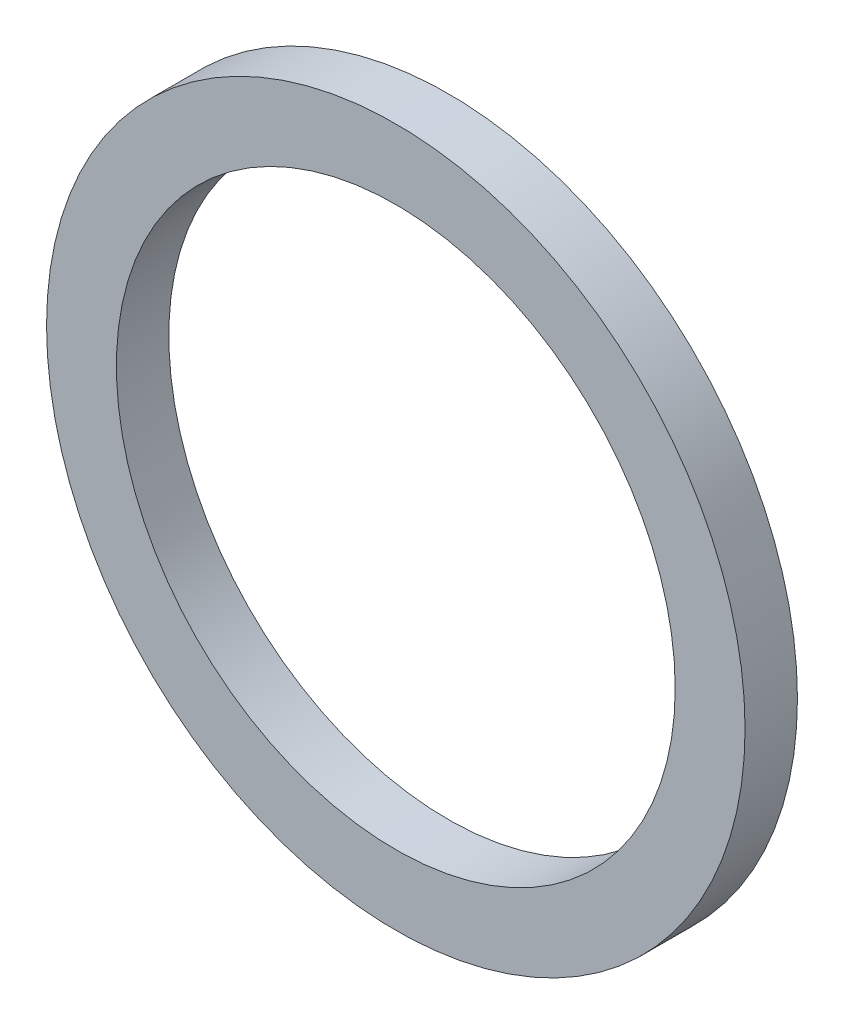
SolidWorks part; units mm, degrees
material "95 AU V142"
ref_plane "Front Plane" through (0, 0, 0) normal (0, 0, 1) x (1, 0, 0)
ref_plane "Top Plane" through (0, 0, 0) normal (0, 1, 0) x (1, 0, 0)
ref_plane "Right Plane" through (0, 0, 0) normal (1, 0, 0) x (0, 0, -1)
sketch "Sketch1" plane through (0, 0, 0) normal (1, 0, 0) x (0, 0, -1)
  line L0 (0, 0) -> (5.5802, 0) construction
  line L1 (0, 15) -> (0, 12)
  line L2 (0, 12) -> (2.25, 12)
  line L3 (0, 15) -> (2.25, 15)
  arc A0 (2.25, 15) -> (2.25, 12) centre (-1.6279, 13.5) cw
  dimension "D2" = 2.53
  dimension "D1" = 2.25
  dimension "D3" = 30
  dimension "D4" = 24
revolve "Revolve1" add sketch "Sketch1" angle 360 about L0
